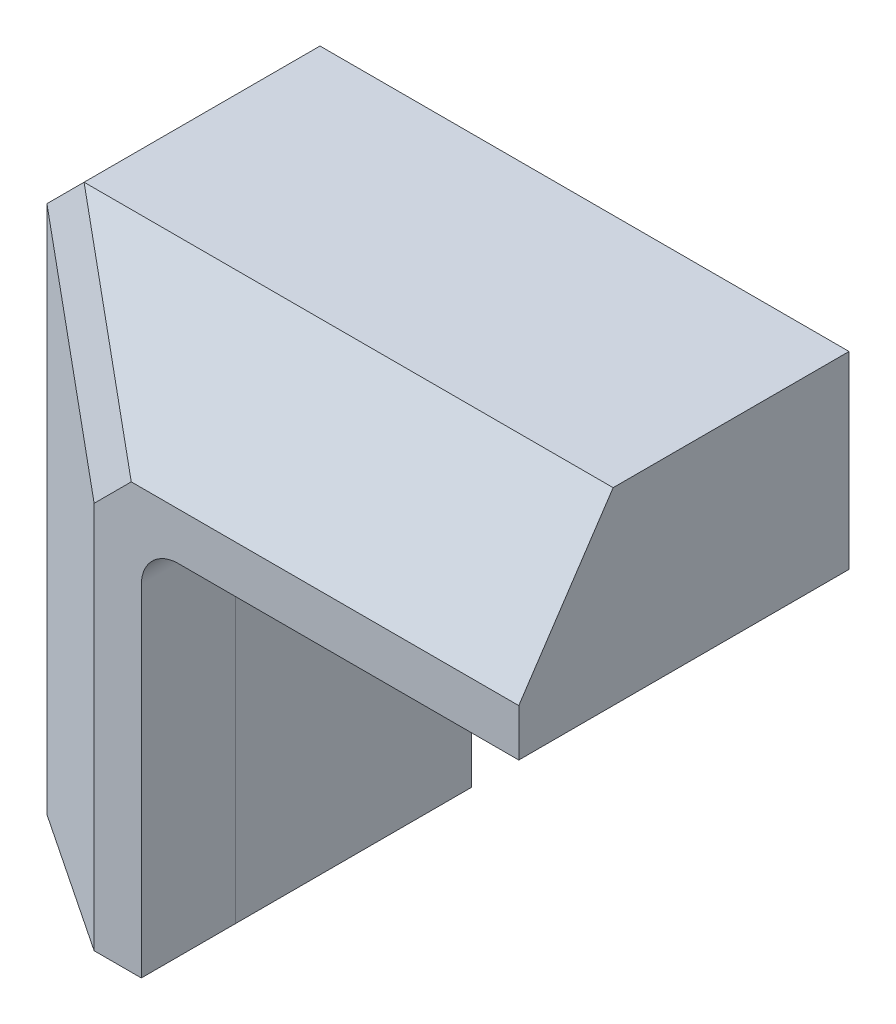
SolidWorks part; units mm, degrees
ref_plane "Front Plane" through (0, 0, 0) normal (0, 0, 1) x (1, 0, 0)
ref_plane "Top Plane" through (0, 0, 0) normal (0, 1, 0) x (1, 0, 0)
ref_plane "Right Plane" through (0, 0, 0) normal (1, 0, 0) x (0, 0, -1)
sketch "Sketch1" plane through (0, 0, 0) normal (0, 0, 1) x (1, 0, 0)
  line L0 (-10.16, 8.161) -> (-8.161, 10.16)
  line L2 (0, -1.999) -> (0, -20.32)
  line L3 (0, -20.32) -> (-10.16, -20.32)
  line L4 (-10.16, 0) -> (-10.16, -20.32)
  line L5 (1.999, 0) -> (20.32, 0)
  line L6 (-10.16, 0) -> (-10.16, 8.161)
  line L7 (-8.161, 10.16) -> (20.32, 10.16)
  line L8 (20.32, 0) -> (20.32, 10.16)
  arc A0 (1.999, 0) -> (0, -1.999) centre (1.999, -1.999) ccw
  point P6 (-10.16, 10.16)
  point P10 (0, 0)
  dimension "D5" = 1.999
  dimension "D1" = 10.16
  dimension "D2" = 10.16
  dimension "D3" = 20.32
  dimension "D4" = 20.32
extrude "Boss-Extrude1" add sketch "Sketch1" along normal blind 12.7
sketch "Sketch2" plane through (0, 0, 12.7) normal (0, 0, 1) x (1, 0, 0)
  line L0 (-10.16, -20.32) -> (0, -20.32)
  line L1 (0, -20.32) -> (0, -1.999)
  line L2 (1.999, 0) -> (20.32, 0)
  line L3 (20.32, 0) -> (20.32, 10.16)
  line L4 (20.32, 10.16) -> (-8.161, 10.16)
  line L5 (-8.161, 10.16) -> (-10.16, 8.161)
  line L6 (-10.16, 8.161) -> (-10.16, -20.32)
  arc A0 (0, -1.999) -> (1.999, 0) centre (1.999, -1.999) cw
ref_plane "Plane1" through (0, 0, 17.78) normal (0, 0, 1) x (1, 0, 0)
sketch "Sketch3" plane through (0, 0, 17.78) normal (0, 0, 1) x (1, 0, 0)
  line L0 (0, -20.32) -> (0, -1.999)
  line L1 (1.999, 0) -> (20.32, 0)
  line L2 (20.32, 0) -> (20.32, 2.54)
  line L3 (20.32, 0) -> (20.32, 10.16) construction
  line L4 (20.32, 2.54) -> (-0.541, 2.54)
  line L5 (-2.54, 0.541) -> (-2.54, -20.32)
  line L6 (-10.16, -20.32) -> (0, -20.32) construction
  line L7 (-2.54, -20.32) -> (0, -20.32)
  line L8 (-0.541, 2.54) -> (-2.54, 0.541)
  arc A0 (0, -1.999) -> (1.999, 0) centre (1.999, -1.999) cw
  point P13 (-2.54, 2.54)
  dimension "D1" = 2.54
  dimension "D2" = 2.54
loft "Loft1" add profiles "Sketch2", "Sketch3"
sketch "Sketch4" plane through (0, 0, 0) normal (0, 0, 1) x (1, 0, 0)
  line L0 (0, 2.54) -> (20.32, 2.54) construction
  line L1 (20.32, 0) -> (20.32, 10.16) construction
  line L2 (1.999, 0) -> (20.32, 0) construction
  text T0 "<b>SCALES</b>"
  dimension "D1" = 2.54
extrude "Cut-Extrude1" cut sketch "Sketch4" along normal blind 2.54
